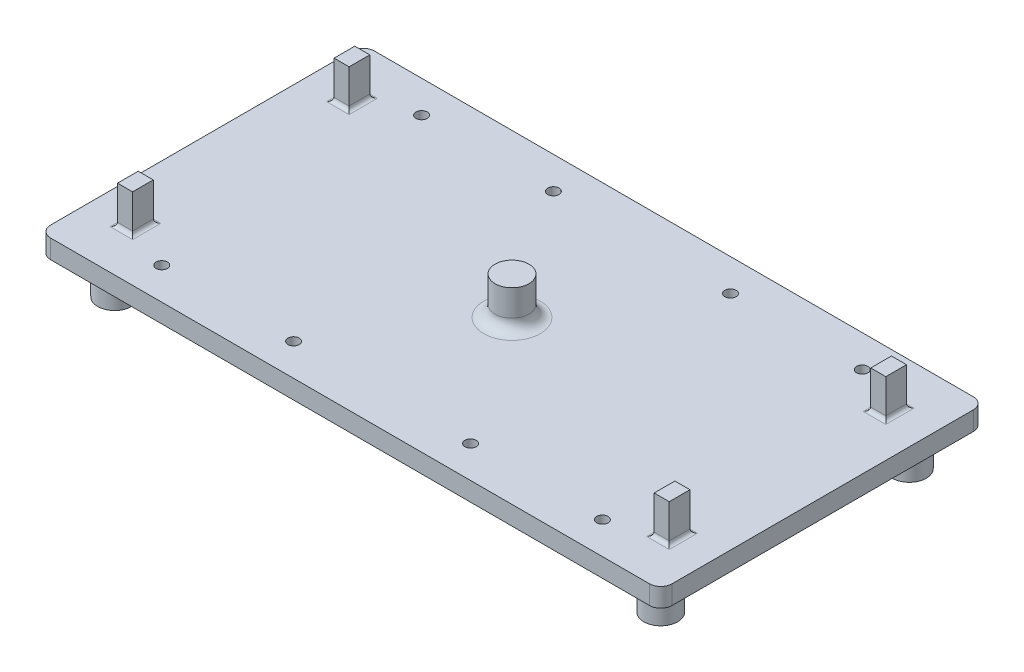
SolidWorks part; units mm, degrees
ref_plane "Front Plane" through (0, 0, 0) normal (0, 0, 1) x (1, 0, 0)
ref_plane "Top Plane" through (0, 0, 0) normal (0, 1, 0) x (1, 0, 0)
ref_plane "Right Plane" through (0, 0, 0) normal (1, 0, 0) x (0, 0, -1)
sketch "Sketch1" plane through (0, 0, 0) normal (0, 1, 0) x (1, 0, 0)
  line L1 (-82.5, 43) -> (82.5, 43)
  line L2 (-82.5, 43) -> (-82.5, -43)
  line L3 (-82.5, -43) -> (82.5, -43)
  line L4 (82.5, 43) -> (82.5, -43)
  line L5 (-82.5, 43) -> (82.5, -43) construction
  line L6 (-82.5, -43) -> (82.5, 43) construction
  point P0 (0, 0)
  dimension "D1" = 165
  dimension "D2" = 86
extrude "Boss-Extrude1" add sketch "Sketch1" along normal blind 5
sketch "Sketch2" plane through (0, 0, 0) normal (0, -1, 0) x (1, 0, 0)
  line L0 (-82.5, 43) -> (82.5, 43) construction
  line L1 (-82.5, -43) -> (-82.5, 43) construction
  line L2 (82.5, -43) -> (-82.5, -43) construction
  line L3 (82.5, 43) -> (82.5, -43) construction
  circle A0 centre (-72.5, 33) radius 10
  circle A1 centre (72.5, 33) radius 10
  circle A2 centre (-72.5, -33) radius 10
  circle A3 centre (72.5, -33) radius 10
  circle A4 centre (-72.5, 33) radius 4.5
  circle A5 centre (72.5, 33) radius 4.5
  circle A6 centre (-72.5, -33) radius 4.5
  circle A7 centre (72.5, -33) radius 4.5
  dimension "D1" = 20
  dimension "D2" = 9
extrude "Boss-Extrude2" add sketch "Sketch2" along normal blind 10 contours A4 | A5 | A7 | A6
fillet "Fillet1" radius 3 4 edges at (72.5, 0, 37.5) (72.5, 0, -28.5) (-72.5, 0, -28.5) (-72.5, 0, 37.5)
sketch "Sketch3" plane through (0, 5, 0) normal (0, 1, 0) x (1, 0, 0)
  line L0 (82.5, -43) -> (82.5, 43) construction
  line L1 (76.25, -37.5) -> (66.25, -37.5)
  line L2 (76.25, -37.5) -> (76.25, 37.5)
  line L3 (76.25, 37.5) -> (66.25, 37.5)
  line L4 (66.25, -37.5) -> (66.25, 37.5)
  line L5 (76.25, -37.5) -> (66.25, 37.5) construction
  line L6 (76.25, 37.5) -> (66.25, -37.5) construction
  line L7 (-82.5, -43) -> (82.5, -43) construction
  line L9 (76.25, -20) -> (66.25, -20)
  line L10 (76.25, -20) -> (76.25, 20)
  line L11 (76.25, 20) -> (66.25, 20)
  line L12 (66.25, -20) -> (66.25, 20)
  line L13 (76.25, -20) -> (66.25, 20) construction
  line L14 (76.25, 20) -> (66.25, -20) construction
  line L15 (73.25, -31.5) -> (69.25, -31.5)
  line L16 (73.25, -31.5) -> (73.25, -26)
  line L17 (73.25, -26) -> (69.25, -26)
  line L18 (69.25, -31.5) -> (69.25, -26)
  line L19 (73.25, -31.5) -> (69.25, -26) construction
  line L20 (73.25, -26) -> (69.25, -31.5) construction
  line L21 (73.25, 26) -> (69.25, 26)
  line L22 (73.25, 26) -> (73.25, 31.5)
  line L23 (73.25, 31.5) -> (69.25, 31.5)
  line L24 (69.25, 26) -> (69.25, 31.5)
  line L25 (73.25, 26) -> (69.25, 31.5) construction
  line L26 (73.25, 31.5) -> (69.25, 26) construction
  circle A0 centre (0, 0) radius 4.5
  point P4 (71.25, 0)
  point P12 (71.25, 0)
  point P17 (71.25, -26)
  point P18 (71.25, -28.75)
  point P23 (71.25, 28.75)
  dimension "D1" = 9
  dimension "D2" = 75
  dimension "D3" = 10
  dimension "D4" = 6.25
  dimension "D5" = 5.5
  dimension "D6" = 40
  dimension "D7" = 6
  dimension "D8" = 6
  dimension "D9" = 3
  dimension "D10" = 3
  dimension "D11" = 6
  dimension "D12" = 6
  dimension "D13" = 3
  dimension "D14" = 3
extrude "Boss-Extrude3" add sketch "Sketch3" along normal blind 10 contours L18 L15 L16 L17 | L24 L21 L22 L23 | A0
fillet "Fillet2" radius 3 1 edges at (0, 5, 4.5)
fillet "Fillet3" radius 1 8 edges at (71.25, 5, -31.5) (69.25, 5, -28.75) (71.25, 5, -26) (73.25, 5, -28.75) (73.25, 5, 28.75) (71.25, 5, 31.5) (69.25, 5, 28.75) (71.25, 5, 26)
mirror "Mirror1" about plane through (0, 0, 0) normal (1, 0, 0) of "Fillet3", "Boss-Extrude3"
fillet "Fillet4" radius 3 4 edges at (-82.5, 2.5, -43) (82.5, 2.5, 43) (82.5, 2.5, -43) (-82.5, 2.5, 43)
sketch "Sketch4" plane through (0, 5, 0) normal (0, 1, 0) x (1, 0, 0)
  line L0 (-82.5, 40) -> (-82.5, -40) construction
  line L1 (-19.5, -37.5) -> (-62.5, -37.5)
  line L2 (-19.5, -37.5) -> (-19.5, 37.5)
  line L3 (-19.5, 37.5) -> (-62.5, 37.5)
  line L4 (-62.5, -37.5) -> (-62.5, 37.5)
  line L5 (-19.5, -37.5) -> (-62.5, 37.5) construction
  line L6 (-19.5, 37.5) -> (-62.5, -37.5) construction
  line L7 (79.5, 43) -> (-79.5, 43) construction
  line L8 (-58.5, -34.5) -> (-23.5, 34.5) construction
  circle A0 centre (-23.5, -34.5) radius 1.5
  circle A1 centre (-58.5, -34.5) radius 1.5
  circle A2 centre (-23.5, 34.5) radius 1.5
  circle A3 centre (-58.5, 34.5) radius 1.5
  point P0 (-41, 0)
  point P11 (-41, 0)
  point P13 (0, 0)
  point P17 (0, 0)
  dimension "D5" = 3
  dimension "D1" = 75
  dimension "D2" = 43
  dimension "D3" = 20
  dimension "D4" = 5.5
  dimension "D6" = 35
  dimension "D7" = 69
extrude "Cut-Extrude1" cut sketch "Sketch4" against normal up to surface (5 mm away) contours A0 | A1 | A3 | A2 up to face at (72.5, 0, 40.5)
mirror "Mirror2" about plane through (0, 0, 0) normal (1, 0, 0) of "Cut-Extrude1"
